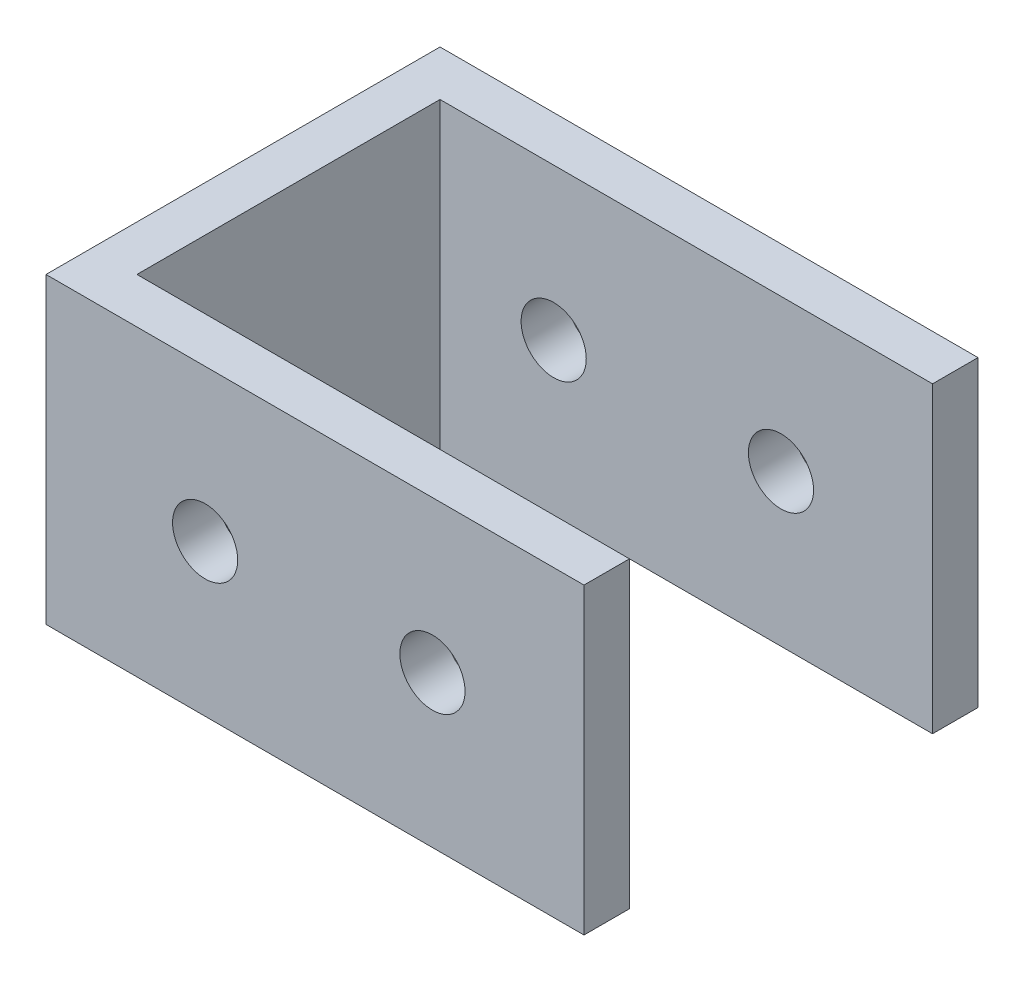
SolidWorks part; units mm, degrees
ref_plane "Front Plane" through (0, 0, 0) normal (0, 0, 1) x (1, 0, 0)
ref_plane "Top Plane" through (0, 0, 0) normal (0, 1, 0) x (1, 0, 0)
ref_plane "Right Plane" through (0, 0, 0) normal (1, 0, 0) x (0, 0, -1)
sketch "Sketch1" plane through (0, 0, 0) normal (0, 1, 0) x (1, 0, 0)
  line L0 (35.5, 23) -> (35.5, 26)
  line L1 (0, 0) -> (35.5, 0)
  line L2 (0, 0) -> (0, 26)
  line L3 (0, 26) -> (35.5, 26)
  line L4 (35.5, 0) -> (35.5, 3)
  line L5 (35.5, 23) -> (3, 23)
  line L7 (35.5, 3) -> (3, 3)
  line L8 (3, 23) -> (3, 3)
  point P9 (3, 13)
  point P10 (0, 13)
  dimension "D1" = 26
  dimension "D2" = 20
  dimension "D3" = 35.5
  dimension "D4" = 3
extrude "Boss-Extrude1" add sketch "Sketch1" along normal blind 20
sketch "Sketch2" plane through (0, 0, 0) normal (0, 0, 1) x (1, 0, 0)
  line L0 (0, 20) -> (0, 0) construction
  circle A0 centre (10.5, 10) radius 2.15
  circle A1 centre (25.5, 10) radius 2.15
  point P7 (0, 10)
  dimension "D1" = 4.3
  dimension "D2" = 15
  dimension "D3" = 10.5
extrude "Cut-Extrude1" cut sketch "Sketch2" against normal through all
